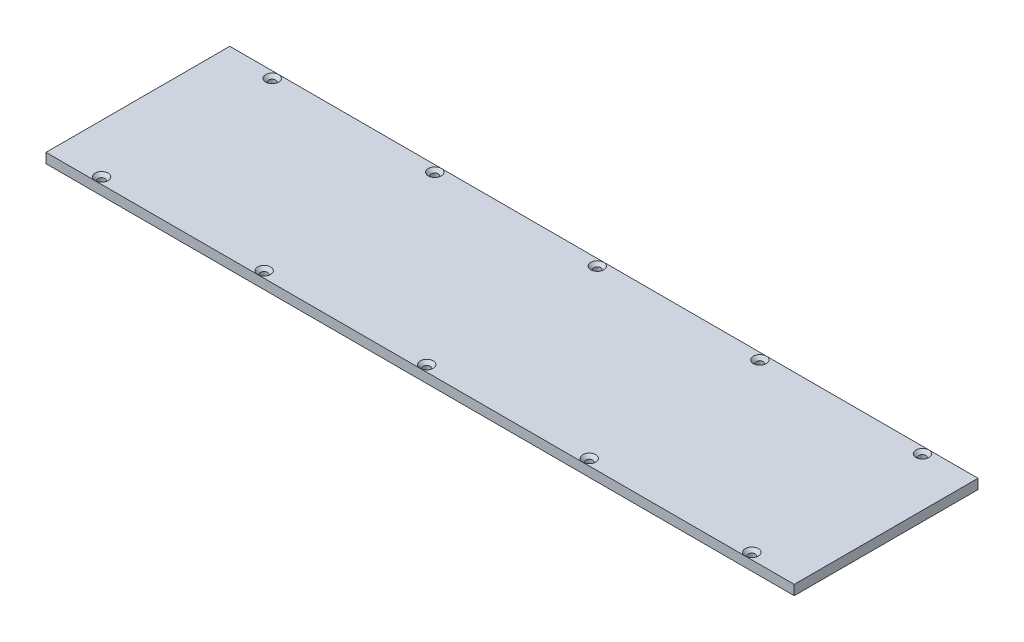
SolidWorks part; units mm, degrees
material "Wood floor laminate, Egger MED"
ref_plane "Front Plane" through (0, 0, 0) normal (0, 0, 1) x (1, 0, 0)
ref_plane "Top Plane" through (0, 0, 0) normal (0, 1, 0) x (1, 0, 0)
ref_plane "Right Plane" through (0, 0, 0) normal (1, 0, 0) x (0, 0, -1)
sketch "Sketch1" plane through (0, 0, 0) normal (0, 1, 0) x (1, 0, 0)
  line L1 (-361.95, -88.9) -> (361.95, -88.9)
  line L2 (-361.95, -88.9) -> (-361.95, 88.9)
  line L3 (-361.95, 88.9) -> (361.95, 88.9)
  line L4 (361.95, -88.9) -> (361.95, 88.9)
  line L5 (0, 88.9) -> (0, -88.9) construction
  line L6 (-361.95, 0) -> (361.95, 0) construction
  point P0 (0, 0)
  dimension "D1" = 723.9
  dimension "D2" = 177.8
extrude "Boss-Extrude1" add sketch "Sketch1" along normal blind 9.525
sketch "Sketch2" plane through (0, 9.525, 0) normal (0, 1, 0) x (1, 0, 0)
  line L0 (-361.95, -88.9) -> (361.95, -88.9) construction
  line L1 (-361.95, -88.9) -> (361.95, -88.9) construction
  line L2 (-361.95, -88.9) -> (-361.95, 88.9) construction
  line L3 (-361.95, 88.9) -> (361.95, 88.9) construction
  line L4 (361.95, -88.9) -> (361.95, 88.9) construction
  line L5 (0, 88.9) -> (0, -88.9) construction
  line L6 (-361.95, 0) -> (361.95, 0) construction
  line L7 (361.95, -88.9) -> (361.95, 88.9) construction
  line L8 (361.95, 88.9) -> (-361.95, 88.9) construction
  line L9 (-361.95, 88.9) -> (-361.95, -88.9) construction
  line L12 (-320.8936, -82.55) -> (320.8936, -82.55) construction
  line L14 (-355.6, -82.55) -> (-355.6, 82.55) construction
  line L15 (355.6, -82.55) -> (355.6, 82.55) construction
  line L16 (-320.8936, 82.55) -> (-320.8936, -82.55) construction
  line L18 (-355.6, 82.55) -> (355.6, 82.55) construction
  line L19 (-355.6, -82.55) -> (355.6, -82.55) construction
  line L20 (320.8936, 82.55) -> (320.8936, -82.55) construction
  line L21 (-314.5436, 82.55) -> (0, 82.55) construction
  line L22 (0, 82.55) -> (314.5436, 82.55) construction
  line L23 (-314.5436, 82.55) -> (-314.5436, -82.55) construction
  line L24 (314.5436, 82.55) -> (314.5436, -82.55) construction
  line L25 (-320.8936, 82.55) -> (-314.5436, 82.55) construction
  line L26 (314.5436, 82.55) -> (320.8936, 82.55) construction
  point P16 (-157.2718, 82.55)
  point P17 (157.2718, 82.55)
  point P19 (-157.2718, -82.55)
  point P20 (157.2718, -82.55)
  point P201 (314.5436, -82.55)
  point P203 (-314.5436, 82.55)
  point P205 (-314.5436, -82.55)
  point P207 (0, -82.55)
  point P209 (0, 82.55)
  point P211 (314.5436, 82.55)
  point P233 (-314.5436, 82.55)
  point P234 (314.5436, 82.55)
  point P235 (314.5436, -82.55)
  point P236 (-314.5436, -82.55)
  dimension "D2" = 320.8936
  dimension "D3" = 320.8936
  dimension "D4" = 6.35
  dimension "D1" = 6.35
  dimension "D5" = 6.35
  dimension "D6" = 6.35
hole_wizard "CSK for M6 Flat Head Machine Screw1" positions "Sketch2" profile "Sketch3" countersink size "M6" standard "ANSI Metric" end condition through all
sketch "Sketch3" plane through (314.5436, 9.525, -82.55) normal (1, 0, 0) x (0, 0, 1)
  line L0 (0, 0) -> (0, 9.525)
  line L1 (0, 9.525) -> (3.3, 9.525)
  line L2 (3.3, 9.525) -> (3.3, 3)
  line L3 (3.3, 3) -> (6.3, 0)
  line L5 (6.3, 0) -> (0, 0)
  line L6 (-3.3, 3) -> (-6.3, 0) construction
  line L11 (0, -6.35) -> (0, 107.95) construction
  dimension "Thru Hole Dia." = 6.6
  dimension "Thru Hole Depth" = 9.525
  dimension "Near C'Sink Dia." = 12.6
  dimension "Near C'Sink Angle" = 90
